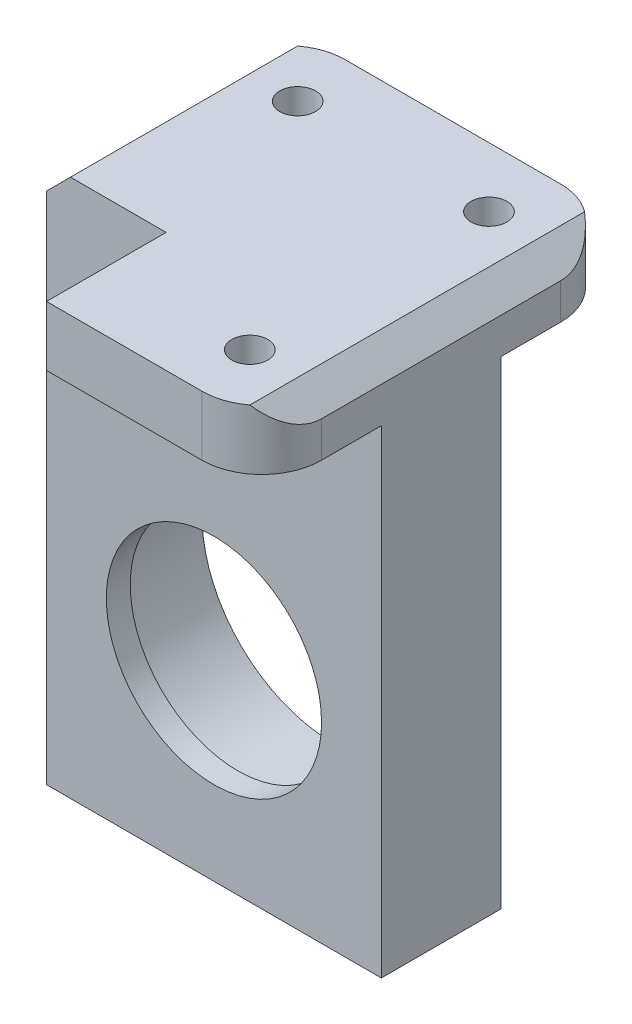
SolidWorks part; units mm, degrees
ref_plane "Alzado" through (0, 0, 0) normal (1, 0, 0) x (0, 1, 0)
ref_plane "Planta" through (0, 0, 0) normal (0, 0, 1) x (0, 1, 0)
ref_plane "Vista lateral" through (0, 0, 0) normal (0, 1, 0) x (-1, 0, 0)
sketch "Croquis1" plane through (0, 0, 0) normal (0, 0, 1) x (0, 1, 0)
  line L1 (-16, -14) -> (29, -14)
  line L2 (-16, -14) -> (-16, 14)
  line L3 (-16, 14) -> (29, 14)
  line L4 (29, -14) -> (29, 14)
  circle A0 centre (0, 0) radius 11
  dimension "D1" = 22
  dimension "D2" = 29
  dimension "D3" = 14
  dimension "D4" = 45
  dimension "D5" = 28
extrude "Saliente-Extruir1" add sketch "Croquis1" along normal blind 10
sketch "Croquis2" plane through (0, 0, 10) normal (0, 0, 1) x (1, 0, 0)
  circle A0 centre (0, 0) radius 11
  circle A1 centre (0, 0) radius 9
  dimension "D1" = 18
extrude "Saliente-Extruir2" add sketch "Croquis2" against normal blind 2
sketch "Croquis3" plane through (0, 29, 0) normal (0, 1, 0) x (1, 0, 0)
  line L0 (-14, -5) -> (14, -5) construction
  line L1 (-14, -10) -> (-14, 0) construction
  line L2 (14, -10) -> (14, 0) construction
  line L3 (0, -5) -> (0, 4.0156) construction
  line L4 (-9, -20) -> (9, -20)
  line L5 (-14, 0) -> (14, 0)
  line L6 (-14, 0) -> (-14, 5)
  line L7 (-9, 10) -> (9, 10)
  line L8 (14, 0) -> (14, 5)
  line L9 (14, -10) -> (14, -15)
  line L10 (-14, -10) -> (14, -10)
  line L11 (-14, -10) -> (-14, -15)
  circle A0 centre (-8, 5) radius 1.5
  circle A1 centre (8, 5) radius 1.5
  arc A2 (9, 10) -> (14, 5) centre (9, 5) cw
  arc A3 (-14, 5) -> (-9, 10) centre (-9, 5) cw
  arc A4 (9, -20) -> (14, -15) centre (9, -15) ccw
  arc A5 (-14, -15) -> (-9, -20) centre (-9, -15) ccw
  circle A6 centre (8, -15) radius 1.5
  circle A7 centre (-8, -15) radius 1.5
  point P21 (-14, 10)
  dimension "D1" = 3
  dimension "D5" = 5
  dimension "D2" = 8
  dimension "D3" = 10
  dimension "D4" = 10
extrude "Saliente-Extruir3" add sketch "Croquis3" against normal blind 5
sketch "Croquis4" plane through (0, 0, 20) normal (0, 0, 1) x (1, 0, 0)
  line L0 (12, 29) -> (14, 27)
  line L1 (14, 29) -> (9, 29) construction
  line L2 (14, 24) -> (14, 29) construction
  line L3 (14, 27) -> (14, 29)
  line L4 (14, 29) -> (12, 29)
  line L5 (0, 29) -> (0, 24) construction
  line L6 (-9, 29) -> (9, 29) construction
  line L7 (-9, 24) -> (9, 24) construction
  line L8 (-14, 27) -> (-14, 29)
  line L9 (-12, 29) -> (-14, 27)
  line L10 (-14, 29) -> (-12, 29)
  dimension "D1" = 2
  dimension "D2" = 2
extrude "Cortar-Extruir1" cut sketch "Croquis4" against normal up to next
sketch "Croquis5" plane through (0, 29, 0) normal (0, 1, 0) x (1, 0, 0)
  line L0 (-14, 5) -> (-14, -15) construction
  line L1 (-14, -10) -> (-4, -10)
  line L2 (-14, -10) -> (-14, -20)
  line L3 (-14, -20) -> (-4, -20)
  line L4 (-4, -10) -> (-4, -20)
  line L5 (-9, -20) -> (9, -20) construction
  dimension "D1" = 10
  dimension "D2" = 10
extrude "Cortar-Extruir2" cut sketch "Croquis5" against normal up to next
